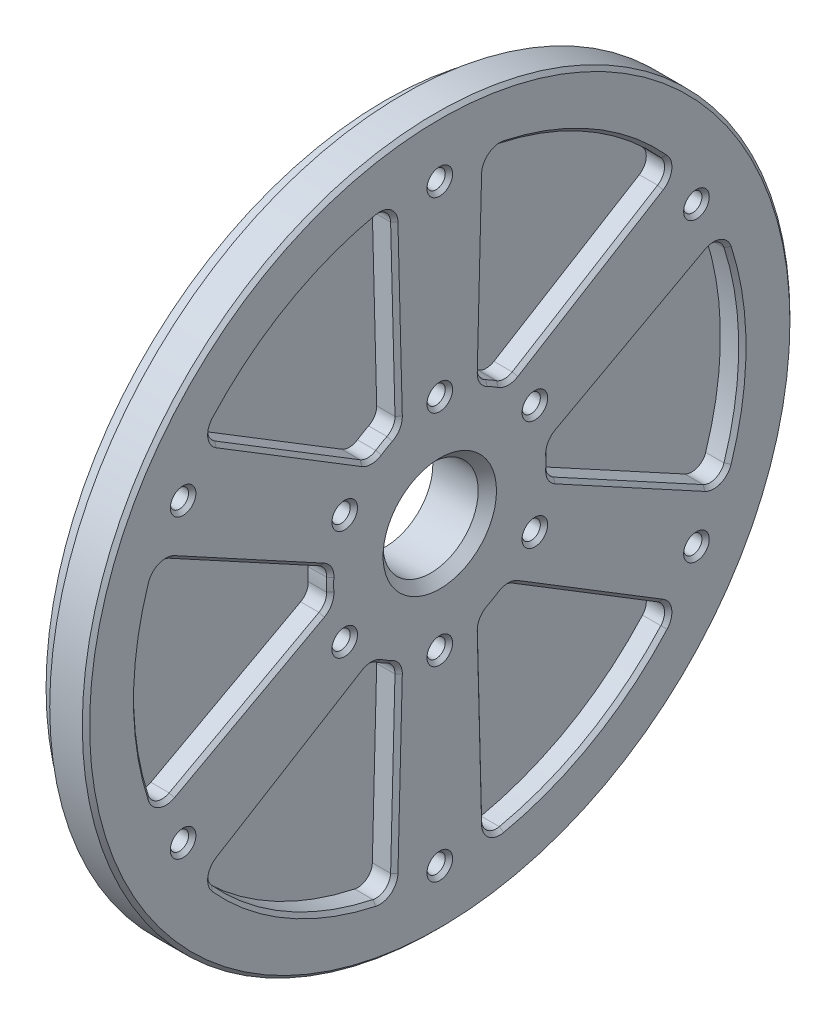
SolidWorks part; units mm, degrees
ref_plane "Front Plane" through (0, 0, 0) normal (0, 0, 1) x (1, 0, 0)
ref_plane "Top Plane" through (0, 0, 0) normal (0, 1, 0) x (1, 0, 0)
ref_plane "Right Plane" through (0, 0, 0) normal (1, 0, 0) x (0, 0, -1)
sketch "Sketch1" plane through (0, 0, 0) normal (1, 0, 0) x (0, 0, -1)
  circle A0 centre (0, 0) radius 48.35
  dimension "D1" = 96.7
extrude "Boss-Extrude1" add sketch "Sketch1" along normal mid plane 5.45
sketch "Sketch3" plane through (2.725, 0, 0) normal (1, 0, 0) x (0, 0, -1)
  line L0 (0, 0) -> (0, 40.5) construction
  circle A0 centre (0, 0) radius 40.5 construction
  circle A1 centre (0, 40.5) radius 1.25
  dimension "D1" = 81
  dimension "D2" = 2.5
extrude "Cut-Extrude1" cut sketch "Sketch3" against normal blind 3
pattern_circular "CirPattern1" count 6 over 360 about axis through (0, 0, 0) along (1, 0, 0) of "Cut-Extrude1"
sketch "Sketch4" plane through (2.725, 0, 0) normal (1, 0, 0) x (0, 0, -1)
  line L0 (0, 0) -> (0, 15) construction
  circle A0 centre (0, 0) radius 15 construction
  circle A1 centre (0, 15) radius 1.25
  dimension "D1" = 30
  dimension "D2" = 2.5
extrude "Cut-Extrude2" cut sketch "Sketch4" against normal blind 3
pattern_circular "CirPattern2" count 6 over 360 about axis through (0, 0, 0) along (1, 0, 0) of "Cut-Extrude2"
sketch "Sketch5" plane through (2.725, 0, 0) normal (1, 0, 0) x (0, 0, -1)
  circle A0 centre (0, 0) radius 6.5
  dimension "D1" = 13
extrude "Cut-Extrude3" cut sketch "Sketch5" against normal up to surface (5.45 mm away) up to face at (-2.725, 0, -48.35)
chamfer "Chamfer1" distance 0.5 angle 45 12 edges at (2.725, -21.3325, -34.449) (2.725, -40.5, 1.25) (2.725, 19.1675, -35.699) (2.725, 6.4175, -13.6154) (2.725, -8.5825, -12.3654) (2.725, -15, 1.25) (2.725, 8.5825, 12.3654) (2.725, -6.4175, 13.6154) (2.725, -19.1675, 35.699) (2.725, 15, -1.25) (2.725, 40.5, -1.25) (2.725, 21.3325, 34.449)
chamfer "Chamfer2" distance 1.25 angle 45 1 edges at (2.725, 0, -6.5)
chamfer "Chamfer3" distance 0.5 angle 45 1 edges at (2.725, 0, -48.35)
sketch "Sketch6" plane through (-2.725, 0, 0) normal (-1, 0, 0) x (0, 0, 1)
  circle A0 centre (0, 0) radius 46.35
  circle A1 centre (0, 0) radius 48.35 construction
  circle A2 centre (0, 0) radius 6.5 construction
  circle A3 centre (0, 0) radius 6.5
  dimension "D1" = 2
extrude "Boss-Extrude2" add sketch "Sketch6" along normal blind 2
sketch "Sketch7" plane through (-2.725, 0, 0) normal (-1, 0, 0) x (0, 0, 1)
  circle A0 centre (0, 0) radius 46.35 construction
  circle A1 centre (0, 0) radius 48.35
  circle A2 centre (0, 0) radius 48.35
  circle A3 centre (0, 0) radius 46.35
  dimension "D1" = 0
extrude "Cut-Extrude4" cut sketch "Sketch7" against normal blind 0.5
sketch "Sketch9" plane through (2.725, 0, 0) normal (1, 0, 0) x (0, 0, -1)
  line L0 (-12.9904, 7.5) -> (0, 15) construction
  line L1 (0, 0) -> (-6.4952, 11.25) construction
  line L2 (-6.4952, 11.25) -> (-7.5, 12.9904) construction
  circle A0 centre (0, 0) radius 47.85 construction
  line B0 (-6.2164, 38.534) -> (-5.6199, 15.2482)
  line B1 (-10.3953, 12.4911) -> (-30.2632, 24.6506)
  arc B2 (-6.7229, 13.4091) -> (-5.6199, 15.2482) centre (-7.6193, 15.1969) ccw
  arc B3 (-6.7229, 13.4091) -> (-8.2512, 12.5267) centre (0, 0) ccw
  arc B4 (-10.3953, 12.4911) -> (-8.2512, 12.5267) centre (-9.3513, 14.1969) ccw
  arc B5 (-30.7042, 27.6961) -> (-30.2632, 24.6506) centre (-29.2192, 26.3565) ccw
  arc B6 (-8.6334, 40.4387) -> (-30.7042, 27.6961) centre (0, 0) ccw
  arc B7 (-6.2164, 38.534) -> (-8.6334, 40.4387) centre (-8.2158, 38.4828) ccw
sketch_block_instance "Block-BLOCK 1 - MOTOR 8 - ROBOT DOG-1"
sketch_block "Block-BLOCK 1 - MOTOR 8 - ROBOT DOG"
extrude "Cut-Extrude6" cut sketch "Sketch9" against normal blind 3
pattern_circular "CirPattern3" count 6 over 360 about axis through (0, 0, 0) along (1, 0, 0) of "Cut-Extrude6"
chamfer "Chamfer4" distance 0.5 angle 45 48 edges at (2.725, -8.3202, 26.2474) (2.725, -1.9711, 15.2221) (2.725, -13.9838, 38.1764) (2.725, 0, 15) (2.725, 0, 41.35) (2.725, 1.9711, 15.2221) (2.725, 13.9838, 38.1764) (2.725, 8.3202, 26.2474) (2.725, -35.8102, -20.675) (2.725, -26.0698, -31.1985) (2.725, -40.0536, -6.9779) (2.725, -18.5708, -20.3293) (2.725, -26.8911, -5.9182) (2.725, -12.1972, -9.3181) (2.725, -14.1683, -5.9041) (2.725, -12.9904, -7.5) (2.725, -26.8911, 5.9182) (2.725, -14.1683, 5.9041) (2.725, -40.0536, 6.9779) (2.725, -12.9904, 7.5) (2.725, -35.8102, 20.675) (2.725, -12.1972, 9.3181) (2.725, -26.0698, 31.1985) (2.725, -18.5708, 20.3293) (2.725, -8.3202, -26.2474) (2.725, -13.9838, -38.1764) (2.725, -1.9711, -15.2221) (2.725, 0, -41.35) (2.725, 0, -15) (2.725, 13.9838, -38.1764) (2.725, 1.9711, -15.2221) (2.725, 8.3202, -26.2474) (2.725, 12.9904, -7.5) (2.725, 12.1972, -9.3181) (2.725, 14.1683, -5.9041) (2.725, 18.5708, -20.3293) (2.725, 26.8911, -5.9182) (2.725, 26.0698, -31.1985) (2.725, 40.0536, -6.9779) (2.725, 35.8102, -20.675) (2.725, 12.9904, 7.5) (2.725, 14.1683, 5.9041) (2.725, 12.1972, 9.3181) (2.725, 26.8911, 5.9182) (2.725, 18.5708, 20.3293) (2.725, 40.0536, 6.9779) (2.725, 26.0698, 31.1985) (2.725, 35.8102, 20.675)
